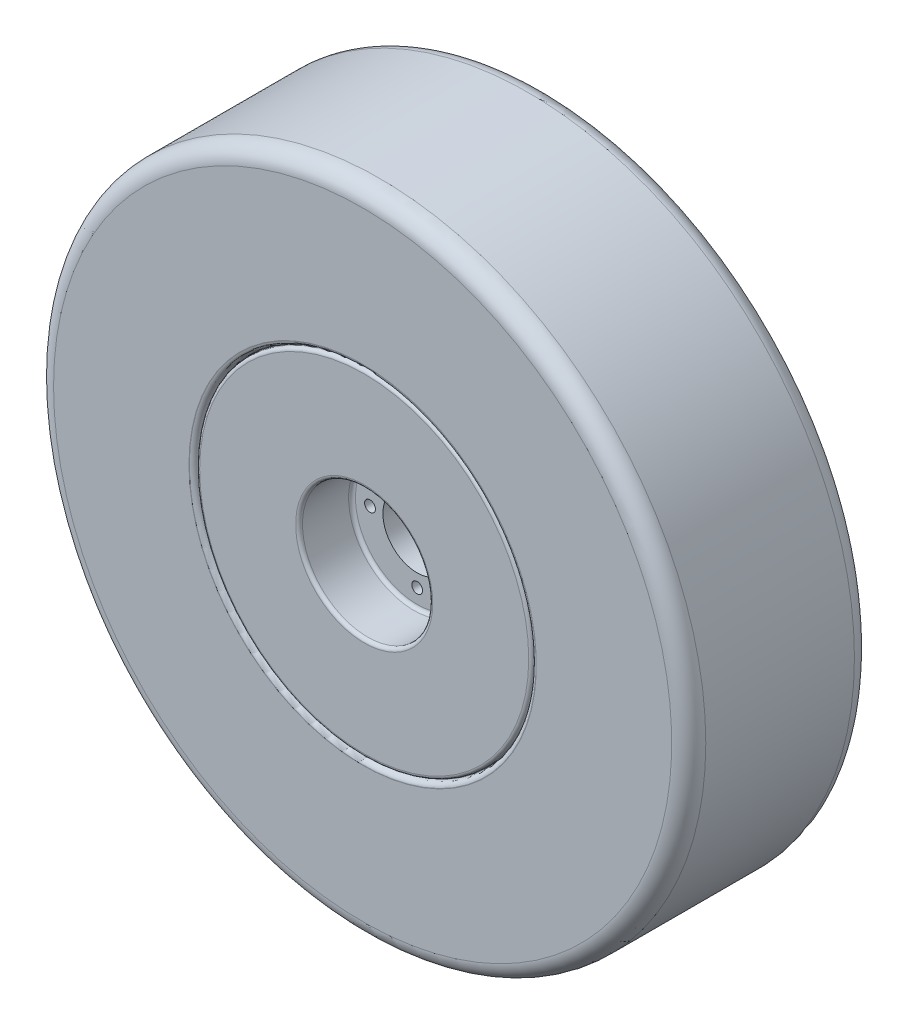
SolidWorks part; units mm, degrees
ref_plane "Alzado" through (0, 0, 0) normal (0, 0, 1) x (1, 0, 0)
ref_plane "Planta" through (0, 0, 0) normal (0, 1, 0) x (1, 0, 0)
ref_plane "Vista lateral" through (0, 0, 0) normal (1, 0, 0) x (0, 0, -1)
sketch "Croquis1" plane through (0, 0, 0) normal (1, 0, 0) x (0, 0, -1)
  line L0 (-41.275, 0) -> (92.075, 0) construction
  line L1 (-2.032, 25.4) -> (52.832, 25.4)
  line L2 (-2.032, 25.4) -> (-2.032, 45.72)
  line L3 (-4.572, 48.26) -> (-38.735, 48.26)
  line L4 (-41.275, 50.8) -> (-41.275, 121.92)
  line L5 (-38.735, 124.46) -> (-31.115, 124.46)
  line L6 (-28.575, 121.92) -> (-28.575, 63.5)
  line L7 (-26.035, 60.96) -> (76.835, 60.96)
  line L8 (25.4, 0) -> (25.4, 99.1389) construction
  line L9 (52.832, 25.4) -> (52.832, 45.72)
  line L10 (55.372, 48.26) -> (89.535, 48.26)
  line L11 (92.075, 50.8) -> (92.075, 121.92)
  line L12 (89.535, 124.46) -> (81.915, 124.46)
  line L13 (79.375, 121.92) -> (79.375, 63.5)
  arc A0 (52.832, 45.72) -> (55.372, 48.26) centre (55.372, 45.72) cw
  arc A1 (-2.032, 45.72) -> (-4.572, 48.26) centre (-4.572, 45.72) ccw
  arc A2 (89.535, 48.26) -> (92.075, 50.8) centre (89.535, 50.8) ccw
  arc A3 (92.075, 121.92) -> (89.535, 124.46) centre (89.535, 121.92) ccw
  arc A4 (81.915, 124.46) -> (79.375, 121.92) centre (81.915, 121.92) ccw
  arc A5 (79.375, 63.5) -> (76.835, 60.96) centre (76.835, 63.5) cw
  arc A6 (-31.115, 124.46) -> (-28.575, 121.92) centre (-31.115, 121.92) cw
  arc A7 (-38.735, 48.26) -> (-41.275, 50.8) centre (-38.735, 50.8) cw
  arc A8 (-41.275, 121.92) -> (-38.735, 124.46) centre (-38.735, 121.92) cw
  arc A9 (-28.575, 63.5) -> (-26.035, 60.96) centre (-26.035, 63.5) ccw
  point P18 (25.4, 60.96)
  point P20 (52.832, 48.26)
  point P23 (-2.032, 48.26)
  point P26 (92.075, 48.26)
  point P29 (92.075, 124.46)
  point P32 (79.375, 124.46)
  point P35 (79.375, 60.96)
  point P38 (-28.575, 124.46)
  point P41 (-41.275, 48.26)
  point P44 (-41.275, 124.46)
  point P47 (-28.575, 60.96)
  dimension "D8" = 2.54
  dimension "D1" = 133.35
  dimension "D2" = 41.275
  dimension "D3" = 12.7
  dimension "D4" = 50.8
  dimension "D5" = 96.52
  dimension "D6" = 76.2
  dimension "D7" = 12.7
revolve "Revolución1" add sketch "Croquis1" angle 360 about L0
sketch "Croquis2" plane through (0, 0, 2.032) normal (0, 0, 1) x (1, 0, 0)
  circle A0 centre (0, 34.925) radius 4.0005
  circle A1 centre (34.925, 0) radius 4.0005
  circle A2 centre (0, -34.925) radius 4.0005
  circle A3 centre (-34.925, 0) radius 4.0005
  point P14 (0, 0)
  dimension "D1" = 8.001
  dimension "D2" = 34.925
  dimension "D3" = 4
extrude "Cortar-Extruir1" cut sketch "Croquis2" against normal through all
sketch "Croquis3" plane through (0, 0, 0) normal (1, 0, 0) x (0, 0, -1)
  line L0 (183.0472, 0) -> (-183.0472, 0)
  line L4 (-30.7747, 124.854) -> (-38.3947, 124.854)
  line L5 (-28.2347, 114.694) -> (-28.2347, 122.314)
  line L6 (79.3612, 121.8693) -> (79.3612, 114.2493)
  line L7 (89.5212, 124.4093) -> (81.9012, 124.4093)
  line L8 (-34.4211, 137.854) -> (-34.4211, 157.5806)
  line L9 (-42.4211, 132.1528) -> (-42.4211, 229.0369)
  line L10 (-29.8011, 241.6569) -> (80.3378, 241.6569)
  line L11 (92.9578, 229.0369) -> (92.9578, 192.1269)
  line L12 (-42.4211, 132.1528) -> (-42.4211, 128.7297)
  line L13 (84.9578, 219.7734) -> (84.9578, 137.4893)
  line L14 (92.9578, 192.1269) -> (92.9578, 128.0023)
  line L15 (-29.4211, 132.854) -> (-26.0399, 132.854)
  line L16 (-20.2347, 127.0489) -> (-20.2347, 114.694)
  line L17 (79.8778, 132.4093) -> (77.1664, 132.4093)
  line L18 (-42.4211, 51.1569) -> (41.6153, 51.1569) construction
  line L21 (71.3612, 126.6041) -> (71.3612, 114.2493)
  line L22 (-25.6947, 112.154) -> (-25.3947, 112.154)
  line L24 (76.8212, 111.7093) -> (74.8678, 111.7093)
  line L25 (-34.4211, 157.5806) -> (-34.4211, 221.4169)
  line L26 (-26.8811, 228.9569) -> (77.4178, 228.9569)
  line L27 (84.9578, 221.4169) -> (84.9578, 219.7734)
  arc A4 (-28.2347, 122.314) -> (-30.7747, 124.854) centre (-30.7747, 122.314) ccw
  arc A5 (-28.2347, 114.694) -> (-25.6947, 112.154) centre (-25.6947, 114.694) ccw
  arc A6 (76.8212, 111.7093) -> (79.3612, 114.2493) centre (76.8212, 114.2493) ccw
  arc A7 (81.9012, 124.4093) -> (79.3612, 121.8693) centre (81.9012, 121.8693) ccw
  arc A8 (-25.3947, 112.154) -> (-20.2347, 114.694) centre (-24.4013, 116.6472) ccw
  arc A9 (-38.3947, 124.854) -> (-42.4096, 128.4882) centre (-38.4117, 128.8701) cw
  arc A10 (-42.4096, 128.4882) -> (-42.4211, 128.7297) centre (-39.8811, 128.7297) cw
  arc A11 (74.8678, 111.7093) -> (71.3612, 114.2493) centre (75.1737, 115.822) cw
  arc A12 (89.5212, 124.4093) -> (92.9578, 128.0023) centre (81.1612, 135.8452) ccw
  arc A13 (77.1664, 132.4093) -> (71.3612, 126.6041) centre (77.1664, 126.6041) ccw
  arc A14 (-26.0399, 132.854) -> (-20.2347, 127.0489) centre (-26.0399, 127.0489) cw
  arc A15 (-34.4211, 137.854) -> (-29.4211, 132.854) centre (-29.4211, 137.854) ccw
  arc A16 (84.9578, 137.4893) -> (79.8778, 132.4093) centre (79.8778, 137.4893) cw
  arc A17 (-26.8811, 228.9569) -> (-34.4211, 221.4169) centre (-26.8811, 221.4169) ccw
  arc A18 (77.4178, 228.9569) -> (84.9578, 221.4169) centre (77.4178, 221.4169) cw
  arc A19 (92.9578, 229.0369) -> (80.3378, 241.6569) centre (80.3378, 229.0369) ccw
  arc A20 (-29.8011, 241.6569) -> (-42.4211, 229.0369) centre (-29.8011, 229.0369) ccw
  point P66 (0, 0)
  dimension "D7" = 8
  dimension "D3" = 8
  dimension "D4" = 8
  dimension "D6" = 8
  dimension "D1" = 2.54
  dimension "D10" = 5.08
  dimension "D11" = 12.7
  dimension "D12" = 7.54
  dimension "D14" = 12.62
  dimension "D15" = 381
  dimension "D8" = 5.8052
  dimension "D9" = 5
  dimension "D13" = 7.54
  dimension "D2" = 8
  dimension "D5" = 8
revolve "Revolución2" add sketch "Croquis3" angle 360 about L0
